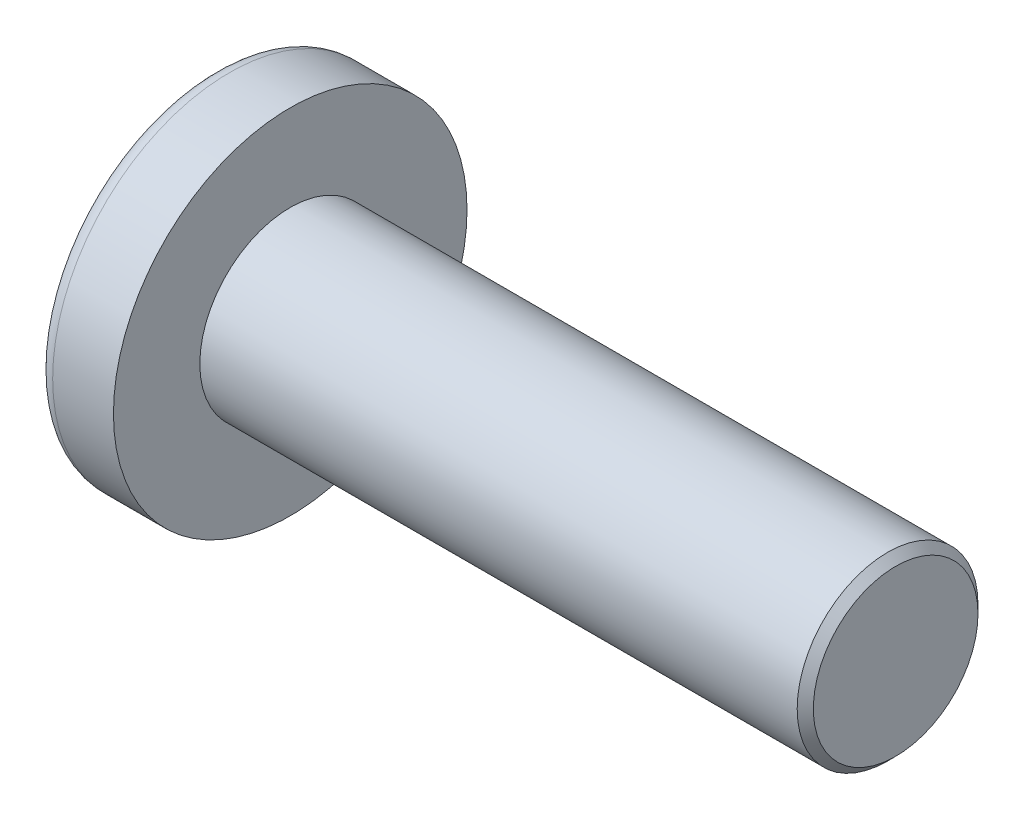
SolidWorks part; units mm, degrees
material "Alloy Steel"
ref_plane "Plane1" through (0, 0, 0) normal (0, 0, 1) x (1, 0, 0)
ref_plane "Plane2" through (0, 0, 0) normal (0, 1, 0) x (1, 0, 0)
ref_plane "Plane3" through (0, 0, 0) normal (1, 0, 0) x (0, 0, -1)
sketch "BodySke" plane through (0, 0, 0) normal (0, 0, 1) x (1, 0, 0)
  line L0 (2.032, 1.4224) -> (2.032, 2.7813)
  line L1 (2.3495, 6.35) -> (2.3495, -3.175) construction
  line L2 (-25.4, 0) -> (127, 0) construction
  line L3 (11.557, 0) -> (0, 0)
  line L4 (2.032, 1.4224) -> (11.557, 1.4224)
  line L5 (11.557, 1.4224) -> (11.557, 0)
  line L6 (1.0756, 2.7813) -> (2.032, 2.7813)
  line L7 (2.032, -1.4224) -> (11.557, -1.4224) construction
  line L8 (2.032, 6.35) -> (2.032, -3.175) construction
  arc A0 (0.8702, 2.6767) -> (0, 0) centre (4.5517, 0) ccw
  arc A2 (0.8702, 2.6767) -> (1.0756, 2.7813) centre (1.0756, 2.5273) cw
  dimension "Head_fillet_rad" = 0.254
  dimension "Head_crown_rad" = 4.5517
  dimension "Head_ht" = 2.032
  dimension "Diameter" = 2.8448
  dimension "Length" = 9.525
  dimension "Head_dia" = 5.5626
  dimension "Advance" = 0.635
  dimension "Thread_nom" = 9.525
revolve "Base-Revolve" add sketch "BodySke" angle 360 about L2
cosmetic thread "ThreadCosmetic" parameters "Thread_length"=8.89, "Thread_minor"=2.0879
sketch "Sketch3" plane through (0, 0, 0) normal (1, 0, 0) x (0, 0, -1)
  line L0 (0.4064, -1.8161) -> (-0.4064, -1.8161)
  line L1 (0.4064, -1.8161) -> (0.4064, 1.8161)
  line L2 (-0.4064, 1.8161) -> (0.4064, 1.8161)
  line L3 (-0.4064, 1.8161) -> (-0.4064, -1.8161)
  dimension "D1" = 1.8161
  dimension "Cross_dia" = 3.6322
  dimension "D2" = 0.4064
  dimension "Cross_width" = 0.8128
ref_plane "Plane4" through (2.0066, 0, 0) normal (1, 0, 0) x (0, 0, -1)
sketch "Sketch4" plane through (2.0066, 0, 0) normal (1, 0, 0) x (0, 0, -1)
  line L0 (0.2032, -0.2032) -> (-0.2032, -0.2032)
  line L1 (0.2032, -0.2032) -> (0.2032, 0.2032)
  line L2 (-0.2032, 0.2032) -> (0.2032, 0.2032)
  line L3 (-0.2032, 0.2032) -> (-0.2032, -0.2032)
  dimension "D1" = 0.4064
  dimension "D2" = 0.4064
  dimension "D3" = 0.2032
  dimension "D4" = 0.2032
loft "Cut-Loft1" cut profiles "Sketch3", "Sketch4"
pattern_circular "CirPattern1" count 2 every 90 about axis through (0, 0, 0) along (1, 0, 0) of "Cut-Loft1"
chamfer "Chamfer1" distance 0.127 angle 45 1 edges at (11.557, 0, 1.4224)
equation "\"D1@Sketch3\" = \"Cross_dia@Sketch3\" / 2"
equation "\"D2@Sketch3\" = \"Cross_width@Sketch3\" / 2"
equation "\"D1@Sketch4\" = \"Cross_width@Sketch3\" *.5"
equation "\"D2@Sketch4\" = \"D1@Sketch4\""
equation "\"D3@Sketch4\" = \"D1@Sketch4\" / 2"
equation "\"D4@Sketch4\" = \"D2@Sketch4\" / 2"
equation "\"Thread_length@ThreadCosmetic\" = ((sgn( (\"Length@BodySke\" - \"Advance@BodySke\" ) - \"Thread_nom@BodySke\" )-1)*( (\"Length@BodySke\" - \"Advance@BodySke\" ) - \"Thread_nom@BodySke\" ))/-2+ \"Thread_nom@BodySke\""
